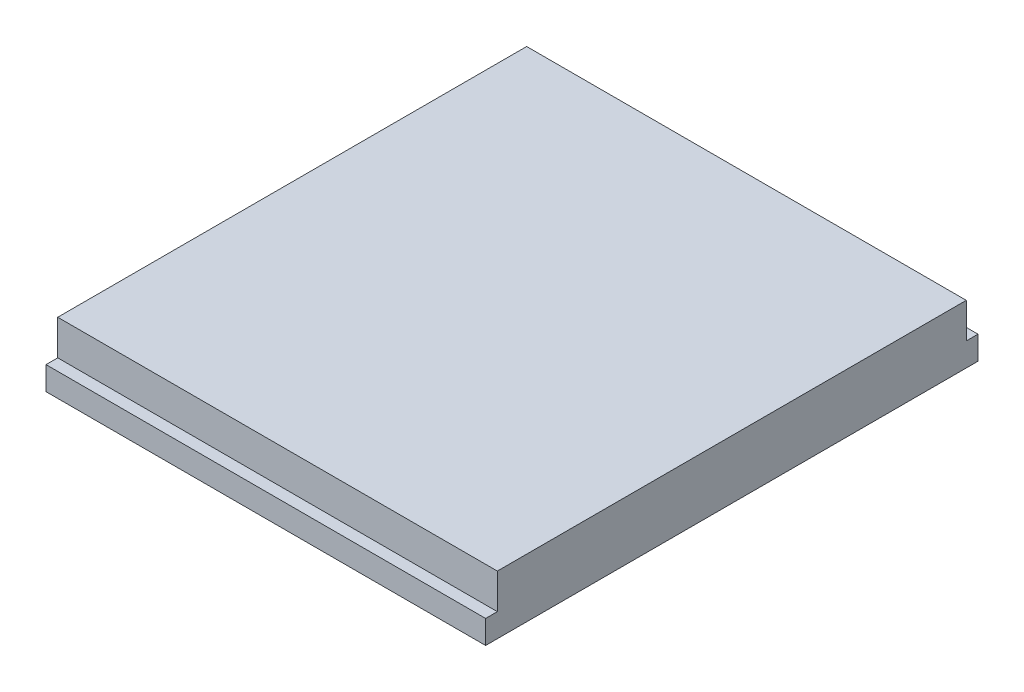
SolidWorks part; units mm, degrees
ref_plane "Front Plane" through (0, 0, 0) normal (0, 0, 1) x (1, 0, 0)
ref_plane "Top Plane" through (0, 0, 0) normal (0, 1, 0) x (1, 0, 0)
ref_plane "Right Plane" through (0, 0, 0) normal (1, 0, 0) x (0, 0, -1)
sketch "Sketch1" plane through (0, 0, 0) normal (0, 1, 0) x (1, 0, 0)
  line L1 (-18.75, -21) -> (18.75, -21)
  line L2 (-18.75, -21) -> (-18.75, 21)
  line L3 (-18.75, 21) -> (18.75, 21)
  line L4 (18.75, -21) -> (18.75, 21)
  line L5 (-18.75, -21) -> (18.75, 21) construction
  line L6 (-18.75, 21) -> (18.75, -21) construction
  point P0 (0, 0)
  point P6 (0, 0)
extrude "Boss-Extrude1" add sketch "Sketch1" along normal blind 5 contours L2 L3 L4 L1
sketch "Sketch2" plane through (0, 5, 0) normal (0, 1, 0) x (1, 0, 0)
  line L0 (18.75, -21) -> (18.75, 21) construction
  line L1 (-18.75, -21) -> (18.75, -21)
  line L2 (-18.75, -21) -> (-18.75, -20)
  line L3 (-18.75, -20) -> (18.75, -20)
  line L4 (18.75, -21) -> (18.75, -20)
extrude "Cut-Extrude1" cut sketch "Sketch2" against normal blind 3
sketch "Sketch3" plane through (0, 5, 0) normal (0, 1, 0) x (1, 0, 0)
  line L0 (18.75, -20) -> (18.75, 21) construction
  line L1 (-18.75, 21) -> (18.75, 21)
  line L2 (-18.75, 21) -> (-18.75, 20)
  line L3 (-18.75, 20) -> (18.75, 20)
  line L4 (18.75, 21) -> (18.75, 20)
extrude "Cut-Extrude2" cut sketch "Sketch3" against normal blind 3
